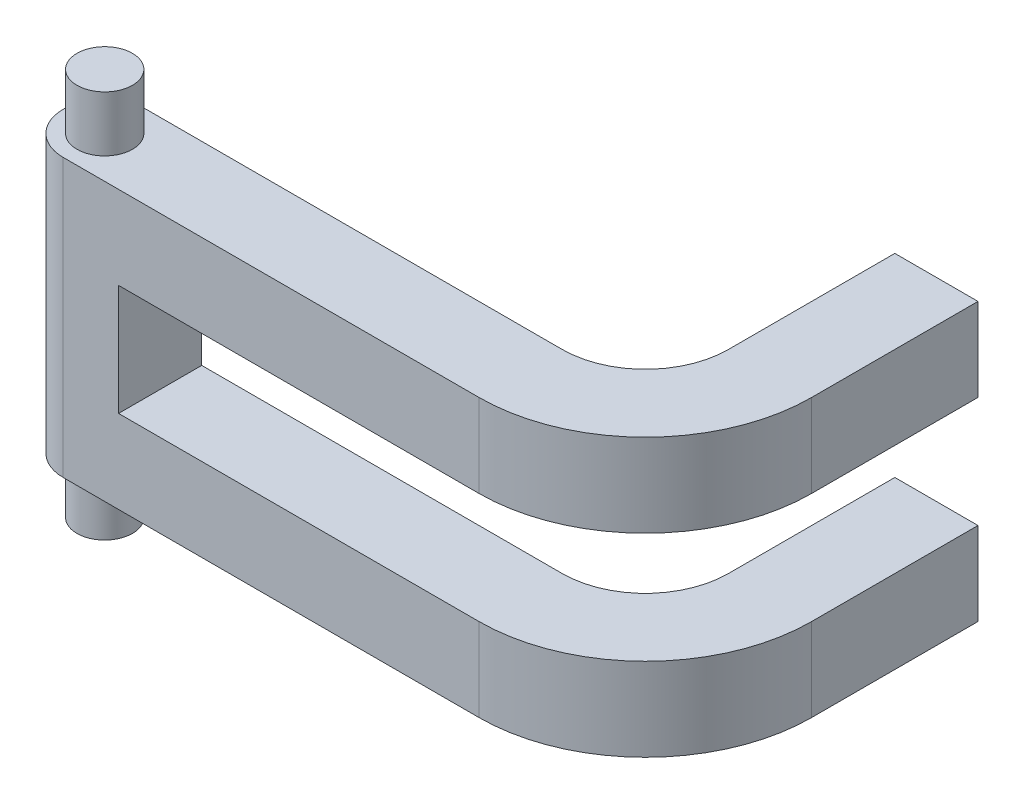
SolidWorks part; units mm, degrees
ref_plane "前视基准面" through (0, 0, 0) normal (0, 0, 1) x (1, 0, 0)
ref_plane "上视基准面" through (0, 0, 0) normal (0, 1, 0) x (1, 0, 0)
ref_plane "右视基准面" through (0, 0, 0) normal (1, 0, 0) x (0, 0, -1)
sketch "草图1" plane through (0, 0, 0) normal (0, 1, 0) x (1, 0, 0)
  line L0 (0, 0) -> (75, 0)
  line L1 (0, 15) -> (75, 15)
  line L4 (90, 30) -> (90, 60)
  line L5 (105, 30) -> (105, 60)
  line L6 (105, 60) -> (90, 60)
  arc A1 (0, 0) -> (0, 15) centre (0, 7.5) cw
  circle A3 centre (0, 7.5) radius 5
  arc A4 (75, 0) -> (105, 30) centre (75, 30) ccw
  arc A5 (75, 15) -> (90, 30) centre (75, 30) ccw
extrude "凸台-拉伸1" add sketch "草图1" along normal blind 42.4983 and the other way blind 7.5
ref_plane "基准面4" through (0, 17.5, 0) normal (0, 1, 0) x (1, 0, 0)
sketch "草图2" plane through (0, 0, 0) normal (0, 1, 0) x (1, 0, 0)
  circle A0 centre (0, 7.5) radius 5
extrude "凸台-拉伸2" add sketch "草图2" against normal mid plane 35
ref_plane "基准面5" through (0, 17.5, 0) normal (0, 1, 0) x (1, 0, 0)
ref_plane "基准面6" through (0, 52.5, 0) normal (0, 1, 0) x (1, 0, 0)
sketch "草图3" plane through (0, 0, 0) normal (0, 1, 0) x (1, 0, 0)
  circle A0 centre (0, 7.5) radius 5
extrude "凸台-拉伸3" add sketch "草图3" along normal up to surface (52.5 mm away) up to plane "基准面6"
ref_plane "基准面7" through (0, 27.5, 0) normal (0, -1, 0) x (-1, 0, 0)
ref_plane "基准面8" through (0, 7.5, 0) normal (0, 1, 0) x (1, 0, 0)
ref_plane "基准面9" through (10, 0, 0) normal (1, 0, 0) x (0, 0, -1)
sketch "草图4" plane through (0, 17.5, 0) normal (0, 1, 0) x (1, 0, 0)
  line L0 (10, -30.6957) -> (10, 30.6957) construction
  line L1 (10, -1.3504) -> (117.7302, -1.3504)
  line L2 (10, -1.3504) -> (10, 73.0086)
  line L3 (10, 73.0086) -> (117.7302, 73.0086)
  line L4 (117.7302, -1.3504) -> (117.7302, 73.0086)
extrude "切除-拉伸1" cut sketch "草图4" against normal mid plane 20
